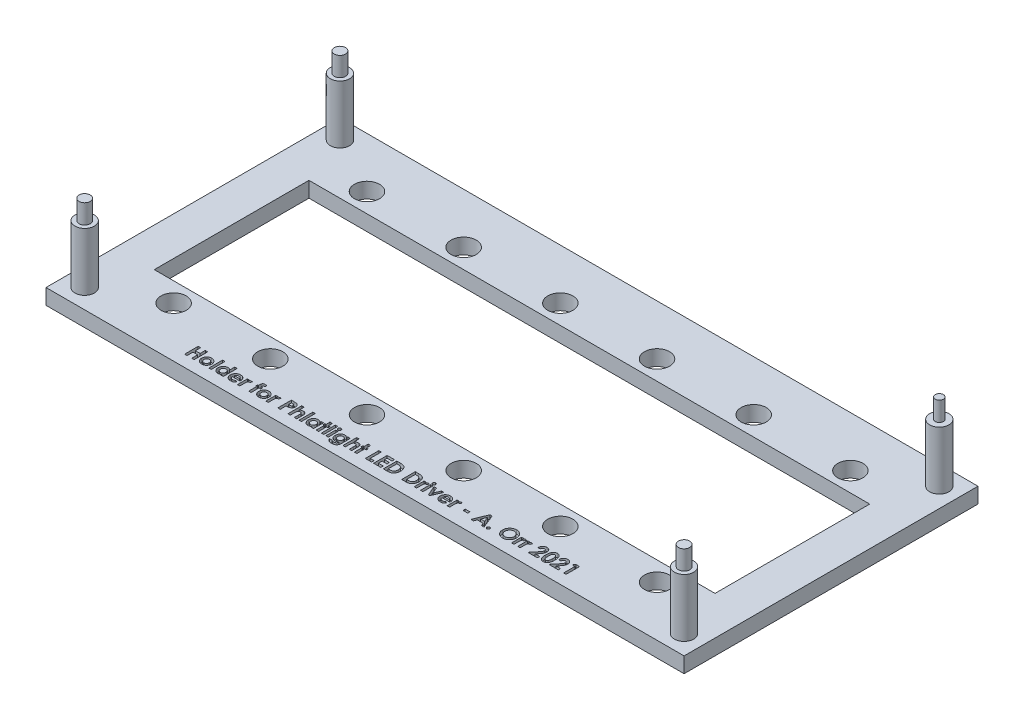
SolidWorks part; units mm, degrees
ref_plane "Front Plane" through (0, 0, 0) normal (0, 0, 1) x (1, 0, 0)
ref_plane "Top Plane" through (0, 0, 0) normal (0, 1, 0) x (1, 0, 0)
ref_plane "Right Plane" through (0, 0, 0) normal (1, 0, 0) x (0, 0, -1)
sketch "Sketch1" plane through (0, 0, 0) normal (0, 1, 0) x (1, 0, 0)
  line L1 (-81.1284, 43.8167) -> (83.8716, 43.8167)
  line L2 (-81.1284, 43.8167) -> (-81.1284, -32.1833)
  line L3 (-81.1284, -32.1833) -> (83.8716, -32.1833)
  line L4 (83.8716, 43.8167) -> (83.8716, -32.1833)
  dimension "D1" = 165
  dimension "D2" = 76
extrude "Boss-Extrude1" add sketch "Sketch1" along normal blind 4
sketch "Sketch2" plane through (0, 4, 0) normal (0, 1, 0) x (1, 0, 0)
  line L0 (-81.1284, 43.8167) -> (-81.1284, -32.1833) construction
  line L1 (-81.1284, -32.1833) -> (83.8716, -32.1833) construction
  line L2 (1.3716, 43.8167) -> (1.3716, -32.1833) construction
  line L3 (83.8716, 43.8167) -> (-81.1284, 43.8167) construction
  line L4 (-81.1284, 5.8167) -> (83.8716, 5.8167) construction
  line L5 (83.8716, -32.1833) -> (83.8716, 43.8167) construction
  circle A0 centre (-76.1284, -27.1833) radius 2.5
  circle A1 centre (78.8716, -27.1833) radius 2.5
  circle A2 centre (78.8716, 38.8167) radius 2.5
  circle A3 centre (-76.1284, 38.8167) radius 2.5
  dimension "D1" = 5
  dimension "D3" = 5
  dimension "D2" = 5
extrude "Boss-Extrude2" add sketch "Sketch2" along normal blind 15
sketch "Sketch3" plane through (0, 19, 0) normal (0, 1, 0) x (1, 0, 0)
  circle A0 centre (78.8716, 38.8167) radius 1.05
  circle A1 centre (-76.1284, -27.1833) radius 1.45
  circle A2 centre (78.8716, -27.1833) radius 1.45
  circle A3 centre (-76.1284, 38.8167) radius 1.45
  dimension "D1" = 2.1
extrude "Boss-Extrude3" add sketch "Sketch3" along normal blind 5
sketch "Sketch4" plane through (0, 4, 0) normal (0, 1, 0) x (1, 0, 0)
  line L0 (83.8716, 43.8167) -> (-81.1284, 43.8167) construction
  line L1 (-11.1284, 30.8167) -> (13.8716, 30.8167) construction
  line L2 (-81.1284, 5.8167) -> (83.8716, 5.8167) construction
  line L3 (-81.1284, 43.8167) -> (-81.1284, -32.1833) construction
  line L4 (83.8716, -32.1833) -> (83.8716, 43.8167) construction
  circle A0 centre (-61.1284, 30.8167) radius 3.25
  circle A1 centre (-36.1284, 30.8167) radius 3.25
  circle A2 centre (-11.1284, 30.8167) radius 3.25
  circle A3 centre (13.8716, 30.8167) radius 3.25
  circle A4 centre (38.8716, 30.8167) radius 3.25
  circle A5 centre (63.8716, 30.8167) radius 3.25
  circle A6 centre (63.8716, -19.1833) radius 3.25
  circle A7 centre (38.8716, -19.1833) radius 3.25
  circle A8 centre (13.8716, -19.1833) radius 3.25
  circle A9 centre (-11.1284, -19.1833) radius 3.25
  circle A10 centre (-36.1284, -19.1833) radius 3.25
  circle A11 centre (-61.1284, -19.1833) radius 3.25
  point P14 (1.3716, 30.8167)
  point P15 (1.3716, 43.8167)
  dimension "D1" = 6.5
  dimension "D3" = 50
  dimension "D2" = 6
extrude "Cut-Extrude1" cut sketch "Sketch4" against normal through all
sketch "Sketch5" plane through (0, 4, 0) normal (0, 1, 0) x (1, 0, 0)
  line L0 (83.8716, 43.8167) -> (-81.1284, 43.8167) construction
  line L1 (-71.1284, 25.8167) -> (73.8716, 25.8167)
  line L2 (-71.1284, 25.8167) -> (-71.1284, -14.1833)
  line L3 (-71.1284, -14.1833) -> (73.8716, -14.1833)
  line L4 (73.8716, 25.8167) -> (73.8716, -14.1833)
  line L5 (-81.1284, 43.8167) -> (-81.1284, -32.1833) construction
  point P4 (1.3716, 25.8167)
  point P7 (1.3716, 43.8167)
  point P8 (-71.1284, 5.8167)
  point P11 (-81.1284, 5.8167)
  dimension "D1" = 40
  dimension "D2" = 145
extrude "Cut-Extrude2" cut sketch "Sketch5" against normal through all
sketch "Sketch6" plane through (0, 4, 0) normal (0, 1, 0) x (1, 0, 0)
  line L0 (-63.6284, -29.1833) -> (66.3716, -29.1833) construction
  line L1 (-81.1284, -32.1833) -> (83.8716, -32.1833) construction
  text T0 "<b>Holder for Phlatlight LED Driver - A. Orr 2021</b>"
  dimension "D1" = 3
extrude "Cut-Extrude3" cut sketch "Sketch6" against normal blind 1
